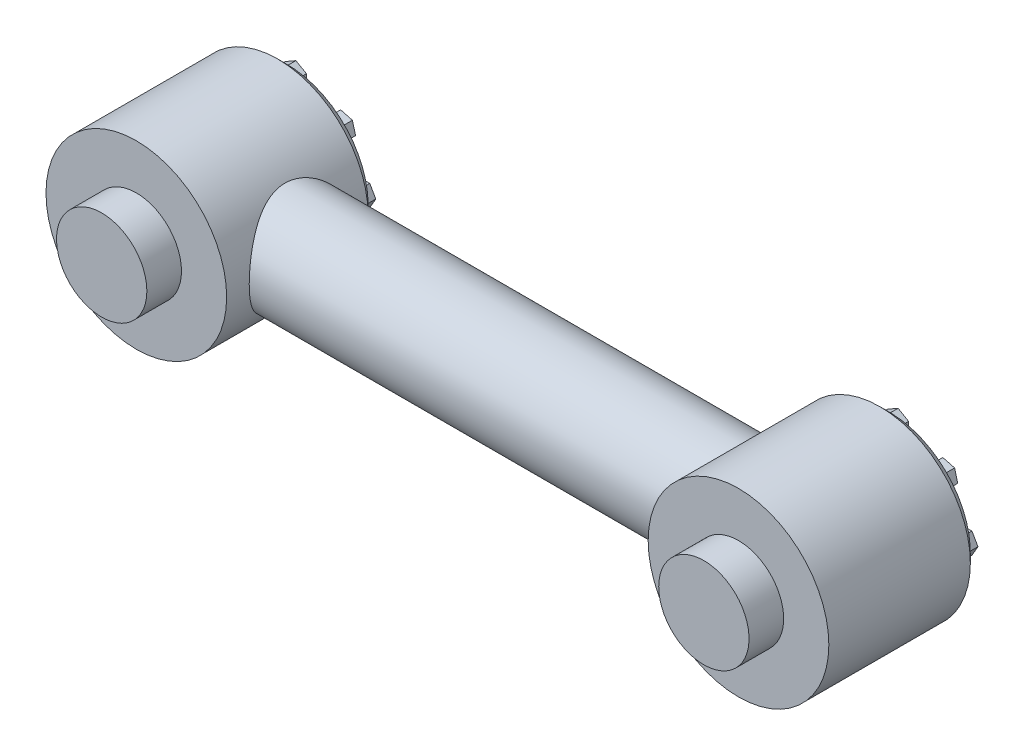
SolidWorks part; units mm, degrees
ref_plane "Ön Düzlem" through (0, 0, 0) normal (0, 0, 1) x (1, 0, 0)
ref_plane "Üst Düzlem" through (0, 0, 0) normal (0, 1, 0) x (1, 0, 0)
ref_plane "Sağ Düzlem" through (0, 0, 0) normal (1, 0, 0) x (0, 0, -1)
sketch "Sketch1" plane through (0, 0, 0) normal (0, 0, 1) x (1, 0, 0)
  line L0 (-100, 0) -> (100, 0) construction
  line L1 (0, -25.7191) -> (0, 45.3866) construction
  circle A0 centre (-100, 0) radius 30
  circle A1 centre (100, 0) radius 30
  dimension "D2" = 60
  dimension "D1" = 200
extrude "Boss-Extrude1" add sketch "Sketch1" along normal mid plane 50
sketch "Sketch2" plane through (0, 0, 0) normal (1, 0, 0) x (0, 0, -1)
  circle A0 centre (0, 0) radius 17.5
  dimension "D1" = 35
extrude "Boss-Extrude2" add sketch "Sketch2" against normal up to body and the other way up to body
sketch "Sketch3" plane through (0, 0, 25) normal (0, 0, 1) x (1, 0, 0)
  circle A0 centre (-100, 0) radius 15
  dimension "D1" = 30
extrude "Boss-Extrude3" add sketch "Sketch3" along normal blind 11.5
chamfer "Chamfer1" distance 3 angle 45 2 edges at (-70, 0, -25) (70, 0, -25)
sketch "Sketch5" plane through (0, 0, -25) normal (0, 0, -1) x (-1, 0, 0)
  line L0 (100, 27) -> (100, -27) construction
  line L1 (73, 0) -> (127, 0) construction
  line L2 (118.7687, 18.7687) -> (114.8649, 19.8147)
  line L3 (100, 26.5429) -> (96.5, 24.5222)
  line L4 (96.5, 24.5222) -> (96.5, 20.4807)
  line L5 (96.5, 20.4807) -> (100, 18.46)
  line L6 (100, 18.46) -> (103.5, 20.4807)
  line L7 (103.5, 20.4807) -> (103.5, 24.5222)
  line L8 (103.5, 24.5222) -> (100, 26.5429)
  line L9 (114.8649, 19.8147) -> (112.0072, 16.9569)
  line L10 (112.0072, 16.9569) -> (113.0532, 13.0532)
  line L11 (113.0532, 13.0532) -> (116.9569, 12.0072)
  line L12 (116.9569, 12.0072) -> (119.8147, 14.8649)
  line L13 (119.8147, 14.8649) -> (118.7687, 18.7687)
  line L14 (126.5429, 0) -> (124.5222, 3.5)
  line L15 (124.5222, 3.5) -> (120.4807, 3.5)
  line L16 (120.4807, 3.5) -> (118.46, 0)
  line L17 (118.46, 0) -> (120.4807, -3.5)
  line L18 (120.4807, -3.5) -> (124.5222, -3.5)
  line L19 (124.5222, -3.5) -> (126.5429, 0)
  line L20 (118.7687, -18.7687) -> (119.8147, -14.8649)
  line L21 (119.8147, -14.8649) -> (116.9569, -12.0072)
  line L22 (116.9569, -12.0072) -> (113.0532, -13.0532)
  line L23 (113.0532, -13.0532) -> (112.0072, -16.9569)
  line L24 (112.0072, -16.9569) -> (114.8649, -19.8147)
  line L25 (114.8649, -19.8147) -> (118.7687, -18.7687)
  line L26 (100, -26.5429) -> (103.5, -24.5222)
  line L27 (103.5, -24.5222) -> (103.5, -20.4807)
  line L28 (103.5, -20.4807) -> (100, -18.46)
  line L29 (100, -18.46) -> (96.5, -20.4807)
  line L30 (96.5, -20.4807) -> (96.5, -24.5222)
  line L31 (96.5, -24.5222) -> (100, -26.5429)
  line L32 (81.2313, -18.7687) -> (85.1351, -19.8147)
  line L33 (85.1351, -19.8147) -> (87.9928, -16.9569)
  line L34 (87.9928, -16.9569) -> (86.9468, -13.0532)
  line L35 (86.9468, -13.0532) -> (83.0431, -12.0072)
  line L36 (83.0431, -12.0072) -> (80.1853, -14.8649)
  line L37 (80.1853, -14.8649) -> (81.2313, -18.7687)
  line L38 (73.4571, 0) -> (75.4778, -3.5)
  line L39 (75.4778, -3.5) -> (79.5193, -3.5)
  line L40 (79.5193, -3.5) -> (81.54, 0)
  line L41 (81.54, 0) -> (79.5193, 3.5)
  line L42 (79.5193, 3.5) -> (75.4778, 3.5)
  line L43 (75.4778, 3.5) -> (73.4571, 0)
  line L44 (81.2313, 18.7687) -> (80.1853, 14.8649)
  line L45 (80.1853, 14.8649) -> (83.0431, 12.0072)
  line L46 (83.0431, 12.0072) -> (86.9468, 13.0532)
  line L47 (86.9468, 13.0532) -> (87.9928, 16.9569)
  line L48 (87.9928, 16.9569) -> (85.1351, 19.8147)
  line L49 (85.1351, 19.8147) -> (81.2313, 18.7687)
  circle A0 centre (100, 0) radius 27 construction
  circle A1 centre (100, 22.5015) radius 3.5 construction
  point P18 (100, 0)
  dimension "D1" = 7
  dimension "D2" = 18.46
  dimension "D3" = 8
extrude "Boss-Extrude4" add sketch "Sketch5" along normal blind 3
sketch "Sketch6" plane through (0, 0, -25) normal (0, 0, -1) x (-1, 0, 0)
  circle A0 centre (100, 0) radius 9.5
  dimension "D1" = 19
extrude "Boss-Extrude5" add sketch "Sketch6" along normal blind 4 draft 6
mirror "Mirror1" about plane through (0, 0, 0) normal (1, 0, 0) of "Boss-Extrude3", "Boss-Extrude4", "Boss-Extrude5"
